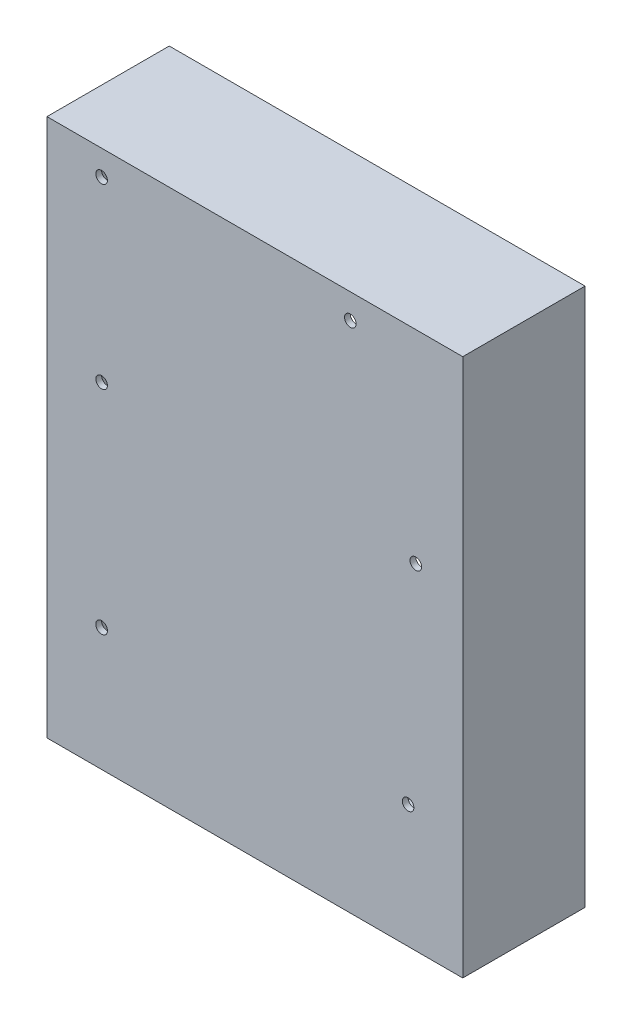
SolidWorks part; units mm, degrees
ref_plane "Front Plane" through (0, 0, 0) normal (0, 0, 1) x (1, 0, 0)
ref_plane "Top Plane" through (0, 0, 0) normal (0, 1, 0) x (1, 0, 0)
ref_plane "Right Plane" through (0, 0, 0) normal (1, 0, 0) x (0, 0, -1)
sketch "Sketch1" plane through (0, 0, 0) normal (0, 0, 1) x (1, 0, 0)
  line L1 (-118.998, 197.3403) -> (96.902, 197.3403)
  line L2 (-118.998, 197.3403) -> (-118.998, -82.0597)
  line L3 (-118.998, -82.0597) -> (96.902, -82.0597)
  line L4 (96.902, 197.3403) -> (96.902, -82.0597)
  dimension "D1" = 215.9
  dimension "D2" = 279.4
extrude "Boss-Extrude1" add sketch "Sketch1" along normal blind 3
sketch "Sketch2" plane through (0, 0, 3) normal (0, 0, 1) x (1, 0, 0)
  line L4 (96.902, -82.0597) -> (96.902, 197.3403) construction
  line L5 (-118.998, -82.0597) -> (96.902, -82.0597) construction
  line L6 (-118.998, 197.3403) -> (-118.998, -82.0597) construction
  line L7 (96.902, 197.3403) -> (-118.998, 197.3403) construction
  line L8 (-115.998, 194.3403) -> (-115.998, -79.0597)
  line L9 (-115.998, -79.0597) -> (93.902, -79.0597)
  line L10 (93.902, -79.0597) -> (93.902, 194.3403)
  line L11 (93.902, 194.3403) -> (-115.998, 194.3403)
  line L12 (-115.998, 194.3403) -> (-115.998, -79.0597)
  line L13 (-115.998, -79.0597) -> (93.902, -79.0597)
  line L14 (93.902, -79.0597) -> (93.902, 194.3403)
  line L15 (93.902, 194.3403) -> (-115.998, 194.3403)
  line L16 (96.902, -82.0597) -> (96.902, 197.3403)
  line L17 (-118.998, -82.0597) -> (96.902, -82.0597)
  line L18 (-118.998, 197.3403) -> (-118.998, -82.0597)
  line L19 (96.902, 197.3403) -> (-118.998, 197.3403)
  dimension "D1" = 3
extrude "Boss-Extrude2" add sketch "Sketch2" against normal blind 63.5
sketch "Sketch3" plane through (0, 0, 0) normal (0, 0, -1) x (-1, 0, 0)
  line L4 (115.998, 194.3403) -> (-93.902, 194.3403)
  line L5 (-93.902, 194.3403) -> (-93.902, -79.0597)
  line L6 (-93.902, -79.0597) -> (115.998, -79.0597)
  line L7 (115.998, -79.0597) -> (115.998, 194.3403)
  line L8 (115.998, 194.3403) -> (-93.902, 194.3403)
  line L9 (-93.902, 194.3403) -> (-93.902, -79.0597)
  line L10 (-93.902, -79.0597) -> (115.998, -79.0597)
  line L11 (115.998, -79.0597) -> (115.998, 194.3403)
  circle A0 centre (-68.517, -18.1797) radius 3
  circle A1 centre (-72.517, 92.0803) radius 3
  circle A2 centre (-38.517, 184.3403) radius 3
  circle A4 centre (90.613, 92.0803) radius 3
  circle A5 centre (-58.712, -93.0942) radius 3
  circle A6 centre (90.613, 184.3403) radius 3
  circle A7 centre (90.613, -18.1797) radius 3.05 construction
  circle A8 centre (90.613, -18.1797) radius 3.05
  dimension "D2" = 6
  dimension "D1" = 0
extrude "Cut-Extrude3" cut sketch "Sketch3" along direction (0, 0, 1) on the side against the normal blind 5 contours A1 | A2 | A0 | A5 | A4 | A6 | A8
